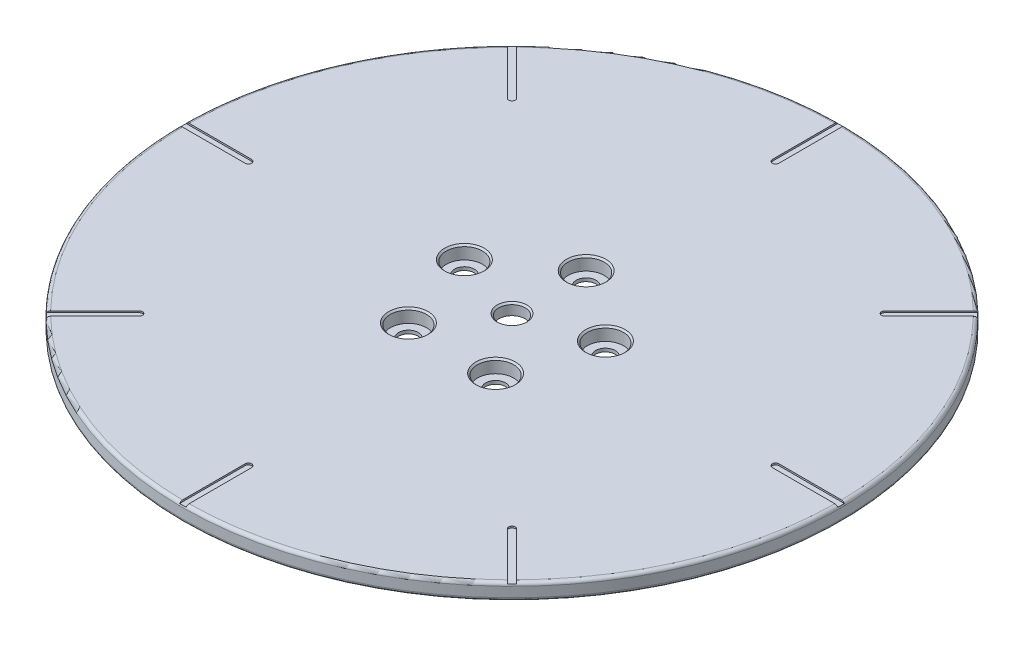
SolidWorks part; units mm, degrees
material "PET"
ref_plane "Přední rovina" through (0, 0, 0) normal (0, 0, 1) x (1, 0, 0)
ref_plane "Horní rovina" through (0, 0, 0) normal (0, 1, 0) x (1, 0, 0)
ref_plane "Pravá rovina" through (0, 0, 0) normal (1, 0, 0) x (0, 0, -1)
sketch "Skica1" plane through (0, 0, 0) normal (0, 0, 1) x (1, 0, 0)
  line L0 (0, 0) -> (0, 58.0429) construction
  line L1 (-4, 0) -> (-4, 5)
  line L2 (-4, 5) -> (-100, 5)
  line L3 (-100, 5) -> (-100, 0)
  line L4 (-100, 0) -> (-4, 0)
  dimension "D1" = 200
  dimension "D2" = 5
  dimension "D3" = 8
revolve "Rotovat1" add sketch "Skica1" angle 360 about L0
sketch "Skica2" plane through (0, 5, 0) normal (0, 1, 0) x (1, 0, 0)
  circle A0 centre (0, 0) radius 22.5 construction
  circle A1 centre (0, 22.5) radius 3
  circle A6 centre (21.3988, 6.9529) radius 3
  circle A7 centre (13.2252, -18.2029) radius 3
  circle A8 centre (-13.2252, -18.2029) radius 3
  circle A9 centre (-21.3988, 6.9529) radius 3
  point P15 (-4.7843, -0.861)
  point P16 (0, 0)
  dimension "D1" = 45
  dimension "D2" = 6
  dimension "D3" = 5
extrude "Odebrat vysunutím1" cut sketch "Skica2" against normal up to surface (5 mm away) contours A1 | A8 | A9 | A6 | A7 up to face at (0, 0, -4)
fillet "Zaoblit1" radius 1 2 edges at (0, 0, -100) (0, 5, -100)
sketch "Skica3" plane through (0, 5, 0) normal (0, 1, 0) x (1, 0, 0)
  circle A0 centre (0, 22.5) radius 5.5
  circle A1 centre (21.3988, 6.9529) radius 5.5
  circle A2 centre (13.2252, -18.2029) radius 5.5
  circle A3 centre (-13.2252, -18.2029) radius 5.5
  circle A4 centre (-21.3988, 6.9529) radius 5.5
  point P13 (0, 0)
  dimension "D1" = 11
  dimension "D2" = 5
extrude "Odebrat vysunutím2" cut sketch "Skica3" against normal blind 4
chamfer "Zkosení2" distance 0.5 angle 45 5 edges at (-13.2252, 5, 23.7029) (13.2252, 5, 23.7029) (21.3988, 5, -1.4529) (0, 5, -17) (-21.3988, 5, -1.4529)
sketch "Skica4" plane through (0, 0, 0) normal (0, -1, 0) x (1, 0, 0)
  circle A0 centre (0, 0) radius 9
  dimension "D1" = 18
extrude "Odebrat vysunutím3" cut sketch "Skica4" against normal blind 1.6
chamfer "Zkosení3" distance 0.5 angle 45 1 edges at (0, 5, -4)
sketch "Skica5" plane through (0, 0, 0) normal (0, -1, 0) x (1, 0, 0)
  line L0 (0, 0) -> (-100, 0) construction
  line L6 (-62.5, -2.5) -> (-57.5, -2.5)
  line L7 (-62.5, -2.5) -> (-62.5, 2.5)
  line L8 (-62.5, 2.5) -> (-57.5, 2.5)
  line L9 (-57.5, -2.5) -> (-57.5, 2.5)
  line L10 (-62.5, -2.5) -> (-57.5, 2.5) construction
  line L11 (-62.5, 2.5) -> (-57.5, -2.5) construction
  circle A0 centre (0, 0) radius 60 construction
  circle A1 centre (0, 0) radius 100 construction
  point P6 (-60, 0)
  dimension "D4" = 120
  dimension "D1" = 60
  dimension "D2" = 5
  dimension "D3" = 5
extrude "Přidat vysunutím1" add sketch "Skica5" along normal blind 10
chamfer "Zkosení8" distance 1 angle 45 8 edges at (-62.5, -10, 0) (-60, -10, 2.5) (-57.5, -10, 0) (-60, -10, -2.5) (-57.5, 0, 0) (-60, 0, -2.5) (-62.5, 0, 0) (-60, 0, 2.5)
sketch "Skica6" plane through (0, 5, 0) normal (0, 1, 0) x (1, 0, 0)
  line L0 (100, 0) -> (-100, 0) construction
  line L1 (-104.8775, 0) -> (-80, 0) construction
  line L2 (-104.8775, 1) -> (-80, 1)
  line L3 (-104.8775, -1) -> (-80, -1)
  line L4 (-74.1596, 74.1596) -> (-56.5685, 56.5685) construction
  line L5 (-73.4525, 74.8667) -> (-55.8614, 57.2756)
  line L6 (-74.8667, 73.4525) -> (-57.2756, 55.8614)
  line L7 (0, 104.8775) -> (0, 80) construction
  line L8 (1, 104.8775) -> (1, 80)
  line L9 (-1, 104.8775) -> (-1, 80)
  line L10 (74.1596, 74.1596) -> (56.5685, 56.5685) construction
  line L11 (74.8667, 73.4525) -> (57.2756, 55.8614)
  line L12 (73.4525, 74.8667) -> (55.8614, 57.2756)
  line L13 (104.8775, 0) -> (80, 0) construction
  line L14 (104.8775, -1) -> (80, -1)
  line L15 (104.8775, 1) -> (80, 1)
  line L16 (74.1596, -74.1596) -> (56.5685, -56.5685) construction
  line L17 (73.4525, -74.8667) -> (55.8614, -57.2756)
  line L18 (74.8667, -73.4525) -> (57.2756, -55.8614)
  line L19 (0, -104.8775) -> (0, -80) construction
  line L20 (-1, -104.8775) -> (-1, -80)
  line L21 (1, -104.8775) -> (1, -80)
  line L22 (-74.1596, -74.1596) -> (-56.5685, -56.5685) construction
  line L23 (-74.8667, -73.4525) -> (-57.2756, -55.8614)
  line L24 (-73.4525, -74.8667) -> (-55.8614, -57.2756)
  circle A0 centre (0, 0) radius 100 construction
  arc A1 (-104.8775, 1) -> (-104.8775, -1) centre (-104.8775, 0) ccw
  arc A2 (-80, -1) -> (-80, 1) centre (-80, 0) ccw
  arc A3 (-73.4525, 74.8667) -> (-74.8667, 73.4525) centre (-74.1596, 74.1596) ccw
  arc A4 (-57.2756, 55.8614) -> (-55.8614, 57.2756) centre (-56.5685, 56.5685) ccw
  arc A5 (1, 104.8775) -> (-1, 104.8775) centre (0, 104.8775) ccw
  arc A6 (-1, 80) -> (1, 80) centre (0, 80) ccw
  arc A7 (74.8667, 73.4525) -> (73.4525, 74.8667) centre (74.1596, 74.1596) ccw
  arc A8 (55.8614, 57.2756) -> (57.2756, 55.8614) centre (56.5685, 56.5685) ccw
  arc A9 (104.8775, -1) -> (104.8775, 1) centre (104.8775, 0) ccw
  arc A10 (80, 1) -> (80, -1) centre (80, 0) ccw
  arc A11 (73.4525, -74.8667) -> (74.8667, -73.4525) centre (74.1596, -74.1596) ccw
  arc A12 (57.2756, -55.8614) -> (55.8614, -57.2756) centre (56.5685, -56.5685) ccw
  arc A13 (-1, -104.8775) -> (1, -104.8775) centre (0, -104.8775) ccw
  arc A14 (1, -80) -> (-1, -80) centre (0, -80) ccw
  arc A15 (-74.8667, -73.4525) -> (-73.4525, -74.8667) centre (-74.1596, -74.1596) ccw
  arc A16 (-55.8614, -57.2756) -> (-57.2756, -55.8614) centre (-56.5685, -56.5685) ccw
  point P7 (-92.4387, 0)
  point P18 (-65.3641, 65.3641)
  point P25 (0, 92.4387)
  point P32 (65.3641, 65.3641)
  point P39 (92.4387, 0)
  point P46 (65.3641, -65.3641)
  point P53 (0, -92.4387)
  point P60 (-65.3641, -65.3641)
  point P65 (0, 0)
  dimension "D1" = 2
  dimension "D2" = 80
  dimension "D3" = 8
extrude "Odebrat vysunutím4" cut sketch "Skica6" against normal blind 0.5
